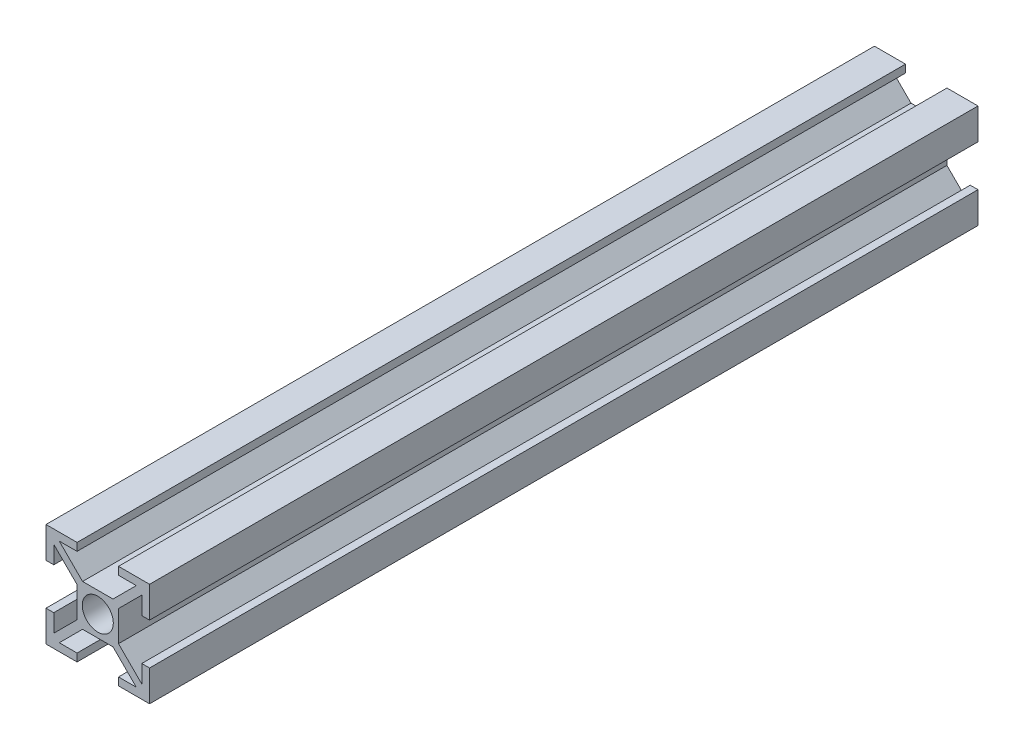
SolidWorks part; units mm, degrees
ref_plane "Plano frontal" through (0, 0, 0) normal (0, 0, 1) x (1, 0, 0)
ref_plane "Plano superior" through (0, 0, 0) normal (0, 1, 0) x (1, 0, 0)
ref_plane "Plano direito" through (0, 0, 0) normal (1, 0, 0) x (0, 0, -1)
sketch "Esboço1" plane through (0, 0, 0) normal (0, 0, 1) x (1, 0, 0)
  line L0 (-2.9393, 4) -> (2.9393, 4)
  line L1 (-10, -10) -> (-4, -10)
  line L2 (-10, -10) -> (-10, -4)
  line L3 (-10, 10) -> (-4, 10)
  line L4 (10, -10) -> (10, -4)
  line L5 (-10, -10) -> (-4, -4) construction
  line L6 (-10, 10) -> (-4, 4) construction
  line L7 (-7.4393, -8.5) -> (-2.9393, -4)
  line L8 (4, -10) -> (10, -10)
  line L9 (-8.5, -7.4393) -> (-4, -2.9393)
  line L10 (-8.5, 7.4393) -> (-4, 2.9393)
  line L11 (-7.4393, -8.5) -> (-4, -8.5)
  line L12 (-8.5, -7.4393) -> (-8.5, -4)
  line L13 (-7.4393, 8.5) -> (-4, 8.5)
  line L14 (8.5, -7.4393) -> (8.5, -4)
  line L15 (-8.5, -8.5) -> (-4, -4) construction
  line L16 (-8.5, 8.5) -> (-4, 4) construction
  line L17 (-4, 10) -> (-4, 8.5)
  line L18 (4, -8.5) -> (7.4393, -8.5)
  line L19 (-10, -4) -> (-8.5, -4)
  line L20 (4, 10) -> (4, 8.5)
  line L21 (-10, 4) -> (-8.5, 4)
  line L22 (-4, 2.9393) -> (-4, -2.9393)
  line L23 (-4, -8.5) -> (-4, -10)
  line L24 (-8.5, 4) -> (-8.5, 7.4393)
  line L25 (-10, 4) -> (-10, 10)
  line L26 (-7.4393, 8.5) -> (-2.9393, 4)
  line L27 (4, 8.5) -> (7.4393, 8.5)
  line L28 (-2.9393, -4) -> (2.9393, -4)
  line L29 (4, 10) -> (10, 10)
  line L30 (4, -8.5) -> (4, -10)
  line L31 (10, 4) -> (10, 10)
  line L32 (8.5, 4) -> (8.5, 7.4393)
  line L33 (-10.5303, -9.4697) -> (9.4697, 10.5303) construction
  line L34 (8.5, 4) -> (10, 4)
  line L35 (8.5, -4) -> (10, -4)
  line L36 (-10, -10) -> (10, 10) construction
  line L37 (4, 2.9393) -> (4, -2.9393)
  line L38 (-9.4697, -10.5303) -> (10.5303, 9.4697) construction
  line L40 (2.9393, -4) -> (7.4393, -8.5)
  line L41 (4, -4) -> (10, -10) construction
  line L42 (4, -4) -> (8.5, -8.5) construction
  line L43 (4, -2.9393) -> (8.5, -7.4393)
  line L44 (4, 0) -> (10, 0) construction
  line L45 (4, 2.9393) -> (8.5, 7.4393)
  line L46 (4, 4) -> (8.5, 8.5) construction
  line L47 (4, 4) -> (10, 10) construction
  line L48 (2.9393, 4) -> (7.4393, 8.5)
  circle A0 centre (0, 0) radius 3
  point P0 (0, 0)
  point P14 (0, 0)
  dimension "D1" = 0.75
  dimension "D3" = 1.5
  dimension "D4" = 20
  dimension "D2" = 0.75
extrude "Ressalto-extrusão1" add sketch "Esboço1" along normal blind 160
